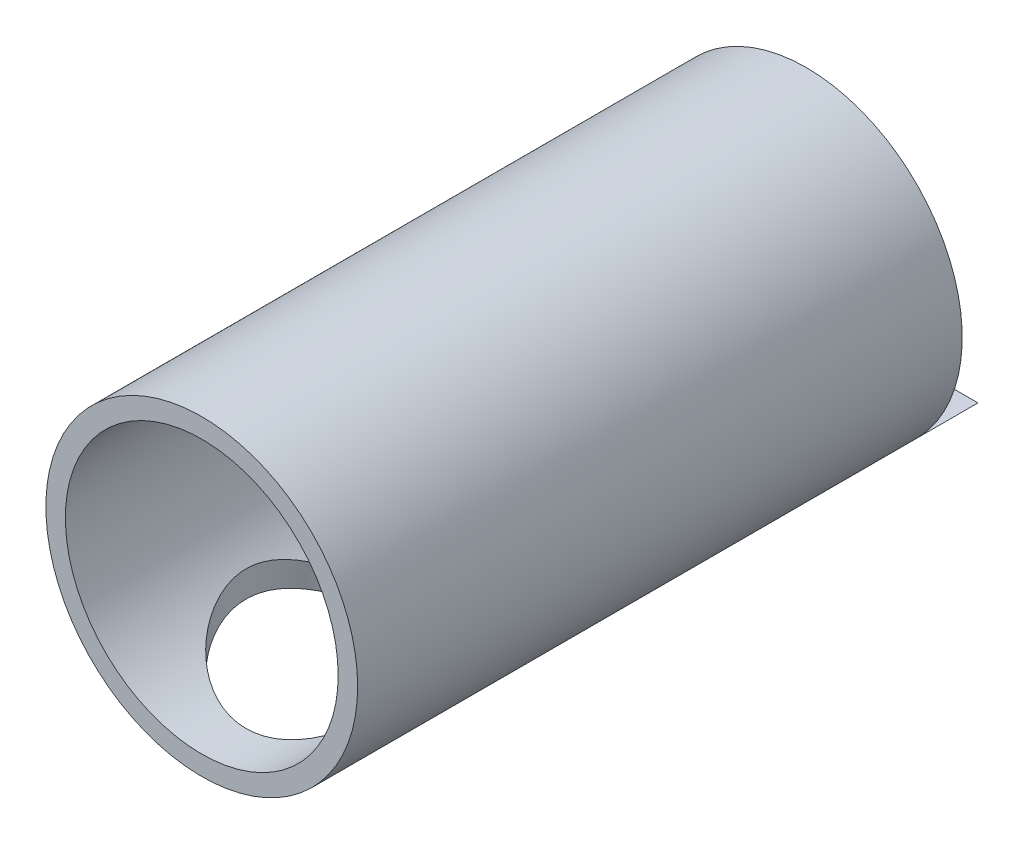
SolidWorks part; units mm, degrees
material "Acrylic (Medium-high impact)"
ref_plane "Front Plane" through (0, 0, 0) normal (0, 0, 1) x (1, 0, 0)
ref_plane "Top Plane" through (0, 0, 0) normal (0, 1, 0) x (1, 0, 0)
ref_plane "Right Plane" through (0, 0, 0) normal (1, 0, 0) x (0, 0, -1)
sketch "Sketch1" plane through (0, 0, 0) normal (0, 0, 1) x (1, 0, 0)
  circle A0 centre (0, 0) radius 25.4
  circle A1 centre (0, 0) radius 22.225
  dimension "D1" = 50.8
  dimension "D2" = 44.45
extrude "Boss-Extrude1" add sketch "Sketch1" along normal blind 914.4
sketch "Sketch2" plane through (0, 0, 0) normal (0, 0, -1) x (-1, 0, 0)
  circle A0 centre (0, 0) radius 25.4 construction
  circle A1 centre (0, 0) radius 25.4
extrude "Cut-Extrude1" cut sketch "Sketch2" against normal through all from offset 130.175 offset against normal yes
ref_plane "Plane1" through (0, -25.4, 0) normal (0, -1, 0) x (-1, 0, 0)
ref_plane "Plane3" through (0, -22.225, 0) normal (0, 1, 0) x (1, 0, 0)
ref_plane "Plane2" through (0, 0, 9.525) normal (0, 0, -1) x (-1, 0, 0)
sketch "Sketch3" plane through (0, 0, 9.525) normal (0, 0, -1) x (-1, 0, 0)
  line L0 (-18.4451, -17.4625) -> (18.4451, -17.4625)
  line L1 (0, -17.4625) -> (0, -25.4) construction
  circle A0 centre (0, 0) radius 25.4 construction
  arc A1 (18.4451, -17.4625) -> (-18.4451, -17.4625) centre (0, 0) ccw
  dimension "D1" = 7.9375
extrude "Cut-Extrude2" cut sketch "Sketch3" along normal through all
ref_plane "Plane4" through (0, 25.4, 0) normal (0, 1, 0) x (1, 0, 0)
sketch "Sketch4" plane through (0, 25.4, 0) normal (0, 1, 0) x (1, 0, 0)
  line L0 (-25.4, -108.0302) -> (-25.4, -130.175)
  line L1 (-25.4, -9.525) -> (-25.4, -130.175) construction
  line L2 (-25.4, -130.175) -> (25.4, -130.175)
  line L3 (25.4, -130.175) -> (25.4, -108.0302)
  line L4 (25.4, -130.175) -> (25.4, -9.525) construction
  line L6 (-25.4, -108.0302) -> (25.4, -108.0302)
  dimension "D1" = 22.1448
extrude "Cut-Extrude3" cut sketch "Sketch4" against normal through all contours L0 L2 L3 L6
ref_plane "Plane5" through (0, -25.4, 0) normal (0, -1, 0) x (-1, 0, 0)
sketch "Sketch5" plane through (0, -25.4, 0) normal (0, -1, 0) x (-1, 0, 0)
  line L1 (119.9836, -78.3583) -> (-126.6492, -138.927) construction
  line L2 (25.4, -101.5864) -> (-25.4, -114.062) construction
  line L3 (-25.4, -68.2986) -> (25.4, -55.823) construction
  line L5 (0, -62.0608) -> (0, -107.8242) construction
  line L6 (-25.4, -9.525) -> (-25.4, -108.0302) construction
  line L7 (25.4, -108.0302) -> (25.4, -9.525) construction
  line L8 (-137.2351, -95.7633) -> (109.3977, -35.1946) construction
  circle A0 centre (0, -84.9425) radius 15.875
  point P17 (0, -107.8242)
  dimension "D1" = 31.75
extrude "Cut-Extrude4" cut sketch "Sketch5" against normal up to surface (3.175 mm away)
